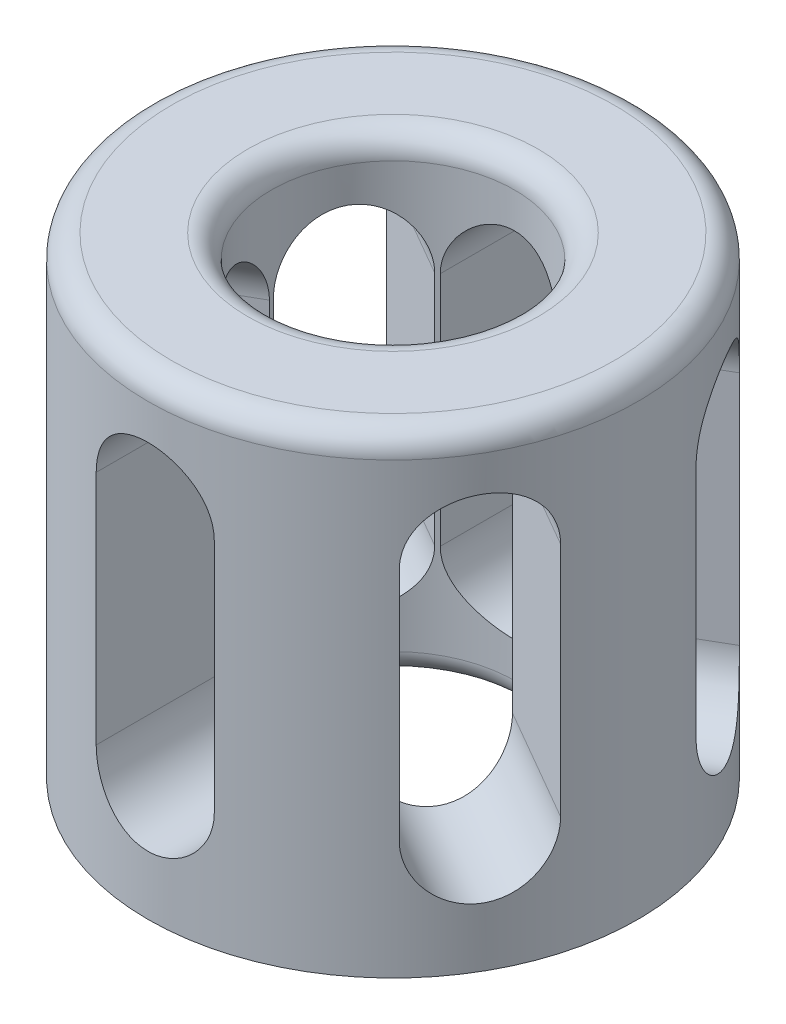
SolidWorks part; units mm, degrees
ref_plane "Front" through (0, 0, 0) normal (0, 0, 1) x (1, 0, 0)
ref_plane "Top" through (0, 0, 0) normal (0, 1, 0) x (1, 0, 0)
ref_plane "Right" through (0, 0, 0) normal (1, 0, 0) x (0, 0, -1)
sketch "Sketch1" plane through (0, 0, 0) normal (0, 1, 0) x (1, 0, 0)
  circle A0 centre (0, 0) radius 20.75
  circle A1 centre (0, 0) radius 10.3
  dimension "D1" = 41.5
  dimension "D2" = 20.6
extrude "Boss-Extrude1" add sketch "Sketch1" along normal blind 40
ref_plane "Plane1" through (0, 0, 20.75) normal (0, 0, 1) x (1, 0, 0)
sketch "Sketch2" plane through (0, 0, 20.75) normal (0, 0, 1) x (1, 0, 0)
  line L0 (0, 40) -> (0, 0) construction
  line L1 (20.75, 40) -> (-20.75, 40) construction
  line L2 (-20.75, 0) -> (20.75, 0) construction
  line L3 (-5, 20) -> (5, 20) construction
  line L4 (-5, 30) -> (5, 30)
  line L5 (-5, 30) -> (-5, 10)
  line L6 (-5, 10) -> (5, 10)
  line L7 (5, 30) -> (5, 10)
  line L8 (-5, 30) -> (5, 10) construction
  line L9 (-5, 10) -> (5, 30) construction
  arc A0 (-5, 30) -> (5, 30) centre (0, 30) cw
  arc A1 (-5, 10) -> (5, 10) centre (0, 10) ccw
  point P6 (0, 20)
  dimension "D1" = 10
  dimension "D2" = 20
extrude "Cut-Extrude1" cut sketch "Sketch2" against normal blind 20 contours L6 A1 | L7 L4 L5 L6 | A0 L4
pattern_circular "CirPattern1" count 6 over 360 about axis through (0, 0, 0) along (0, 1, 0) of "Cut-Extrude1"
fillet "Fillet1" radius 2 3 edges at (0, 40, 20.75) (0, 0, 10.3) (0, 40, 10.3)
